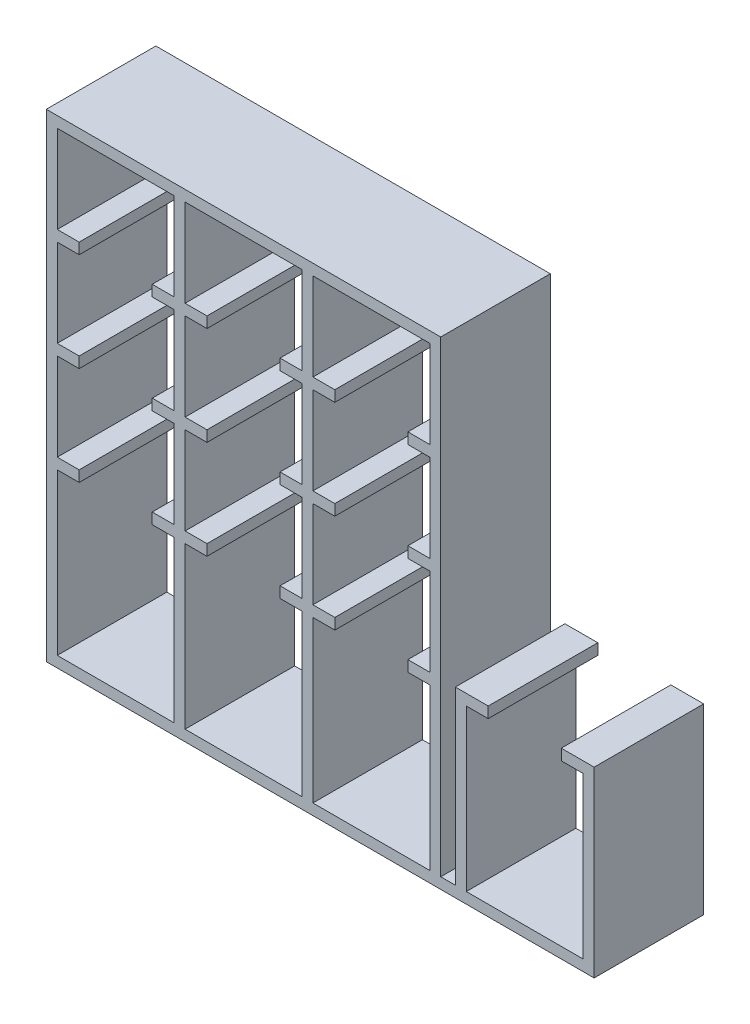
SolidWorks part; units mm, degrees
ref_plane "Front Plane" through (0, 0, 0) normal (0, 0, 1) x (1, 0, 0)
ref_plane "Top Plane" through (0, 0, 0) normal (0, 1, 0) x (1, 0, 0)
ref_plane "Right Plane" through (0, 0, 0) normal (1, 0, 0) x (0, 0, -1)
sketch "Sketch1" plane through (0, 0, 0) normal (0, 0, 1) x (1, 0, 0)
  line L0 (0, 640) -> (540, 640)
  line L1 (540, 640) -> (540, 0)
  line L2 (540, 0) -> (525, 0)
  line L3 (525, 0) -> (525, 220)
  line L4 (525, 220) -> (495, 220)
  line L5 (495, 220) -> (495, 235)
  line L6 (495, 235) -> (525, 235)
  line L7 (525, 235) -> (525, 355)
  line L8 (525, 355) -> (495, 355)
  line L9 (495, 355) -> (495, 370)
  line L10 (495, 370) -> (525, 370)
  line L11 (525, 370) -> (525, 490)
  line L12 (525, 490) -> (495, 490)
  line L13 (495, 490) -> (495, 505)
  line L14 (495, 505) -> (525, 505)
  line L15 (525, 505) -> (525, 625)
  line L16 (525, 625) -> (365, 625)
  line L17 (365, 625) -> (365, 505)
  line L18 (365, 505) -> (395, 505)
  line L19 (395, 505) -> (395, 490)
  line L20 (395, 490) -> (365, 490)
  line L21 (365, 490) -> (365, 370)
  line L22 (365, 370) -> (395, 370)
  line L23 (395, 370) -> (395, 355)
  line L24 (395, 355) -> (365, 355)
  line L25 (365, 355) -> (365, 235)
  line L26 (365, 235) -> (395, 235)
  line L27 (395, 235) -> (395, 220)
  line L28 (395, 220) -> (365, 220)
  line L29 (365, 220) -> (365, 0)
  line L30 (365, 0) -> (350, 0)
  line L31 (350, 0) -> (350, 220)
  line L32 (350, 220) -> (320, 220)
  line L33 (320, 220) -> (320, 235)
  line L34 (320, 235) -> (350, 235)
  line L35 (350, 235) -> (350, 355)
  line L36 (350, 355) -> (320, 355)
  line L37 (320, 355) -> (320, 370)
  line L38 (320, 370) -> (350, 370)
  line L39 (350, 370) -> (350, 490)
  line L40 (350, 490) -> (320, 490)
  line L41 (320, 490) -> (320, 505)
  line L42 (320, 505) -> (350, 505)
  line L43 (350, 505) -> (350, 625)
  line L44 (350, 625) -> (190, 625)
  line L45 (190, 625) -> (190, 505)
  line L46 (190, 505) -> (220, 505)
  line L47 (220, 505) -> (220, 490)
  line L48 (220, 490) -> (190, 490)
  line L49 (190, 490) -> (190, 370)
  line L50 (190, 370) -> (220, 370)
  line L51 (220, 370) -> (220, 355)
  line L52 (220, 355) -> (190, 355)
  line L53 (190, 355) -> (190, 235)
  line L54 (190, 235) -> (220, 235)
  line L55 (220, 235) -> (220, 220)
  line L56 (220, 220) -> (190, 220)
  line L57 (190, 220) -> (190, 0)
  line L58 (190, 0) -> (175, 0)
  line L59 (175, 0) -> (175, 220)
  line L60 (175, 220) -> (145, 220)
  line L61 (145, 220) -> (145, 235)
  line L62 (145, 235) -> (175, 235)
  line L63 (175, 235) -> (175, 355)
  line L64 (175, 355) -> (145, 355)
  line L65 (145, 355) -> (145, 370)
  line L66 (145, 370) -> (175, 370)
  line L67 (175, 370) -> (175, 490)
  line L68 (175, 490) -> (145, 490)
  line L69 (145, 490) -> (145, 505)
  line L70 (145, 505) -> (175, 505)
  line L71 (175, 505) -> (175, 625)
  line L72 (175, 625) -> (15, 625)
  line L73 (15, 625) -> (15, 505)
  line L74 (15, 505) -> (45, 505)
  line L75 (45, 505) -> (45, 490)
  line L76 (45, 490) -> (15, 490)
  line L77 (15, 490) -> (15, 370)
  line L78 (15, 370) -> (45, 370)
  line L79 (45, 370) -> (45, 355)
  line L80 (45, 355) -> (15, 355)
  line L81 (15, 355) -> (15, 235)
  line L82 (15, 235) -> (45, 235)
  line L83 (45, 235) -> (45, 220)
  line L84 (45, 220) -> (15, 220)
  line L85 (15, 220) -> (15, 0)
  line L86 (15, 0) -> (0, 0)
  line L87 (0, 0) -> (0, 640)
  dimension "D1" = 0
  dimension "D2" = 220
  dimension "D3" = 120
  dimension "D4" = 120
  dimension "D5" = 15
  dimension "D6" = 15
  dimension "D7" = 15
  dimension "D8" = 15
  dimension "D9" = 15
  dimension "D10" = 15
  dimension "D11" = 15
  dimension "D12" = 160
  dimension "D13" = 15
  dimension "D14" = 30
  dimension "D17" = 120
extrude "Boss-Extrude1" add sketch "Sketch1" along normal blind 150
sketch "Sketch2" plane through (0, 0, 0) normal (0, 0, 1) x (1, 0, 0)
  line L2 (560, 235) -> (605, 235)
  line L3 (605, 235) -> (605, 220)
  line L4 (605, 220) -> (575, 220)
  line L5 (575, 220) -> (575, 0)
  line L6 (575, 0) -> (560, 0)
  line L7 (735, 0) -> (735, 220)
  line L8 (735, 220) -> (705, 220)
  line L9 (705, 220) -> (705, 235)
  line L10 (705, 235) -> (750, 235)
  line L11 (750, 235) -> (750, 0)
  line L12 (750, 0) -> (735, 0)
  line L13 (525, 235) -> (495, 235) construction
  line L14 (560, 235) -> (560, 0)
  line L15 (540, 0) -> (540, 640) construction
  line L16 (525, 0) -> (540, 0) construction
  dimension "D1" = 15
  dimension "D3" = 20
  dimension "D4" = 45
  dimension "D7" = 15
  dimension "D8" = 100
extrude "Boss-Extrude2" add sketch "Sketch2" along normal blind 150 separate body
sketch "Sketch3" plane through (0, 0, 150) normal (0, 0, 1) x (1, 0, 0)
  line L0 (750, 0) -> (750, 235) construction
  line L1 (0, 0) -> (750, 0)
  line L2 (0, 0) -> (0, -15)
  line L3 (0, -15) -> (750, -15)
  line L4 (750, 0) -> (750, -15)
  dimension "D2" = 15
extrude "Boss-Extrude3" add sketch "Sketch3" against normal blind 150
